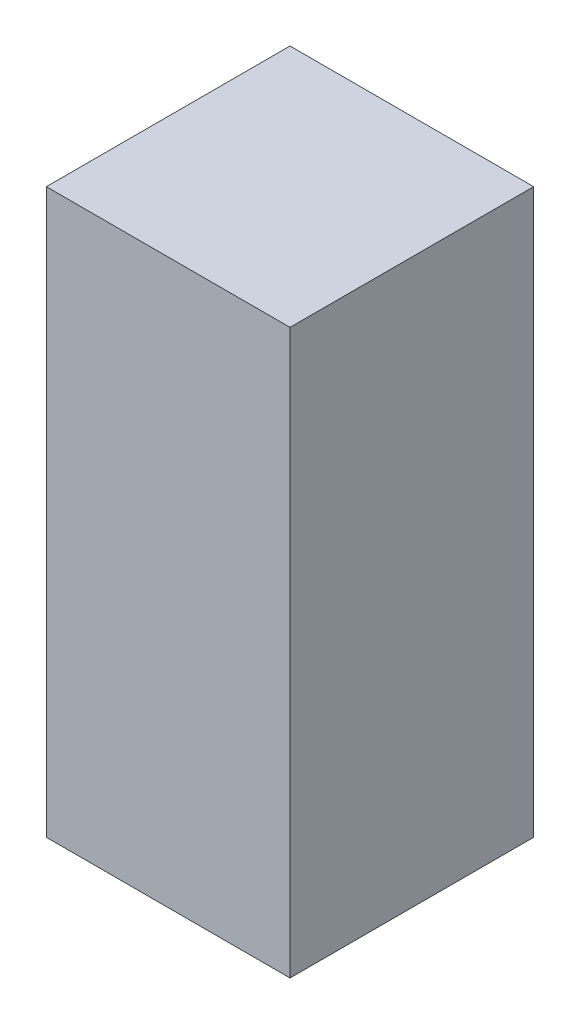
SolidWorks part; units mm, degrees
ref_plane "Front Plane" through (0, 0, 0) normal (0, 0, 1) x (1, 0, 0)
ref_plane "Top Plane" through (0, 0, 0) normal (0, 1, 0) x (1, 0, 0)
ref_plane "Right Plane" through (0, 0, 0) normal (1, 0, 0) x (0, 0, -1)
sketch "Sketch1" plane through (0, 0, 12) normal (0, 0, 1) x (1, 0, 0)
  line L0 (0, 88) -> (0, 0) construction
  line L2 (40, -48.5) -> (-40, -48.5)
  line L3 (40, -48.5) -> (40, 136.5)
  line L4 (40, 136.5) -> (-40, 136.5)
  line L5 (-40, -48.5) -> (-40, 136.5)
  line L6 (40, -48.5) -> (-40, 136.5) construction
  line L7 (40, 136.5) -> (-40, -48.5) construction
  point P4 (0, 44)
  point P5 (0, 44)
  dimension "D1" = 80
  dimension "D2" = 185
extrude "Boss-Extrude1" add sketch "Sketch1" against normal blind 80
